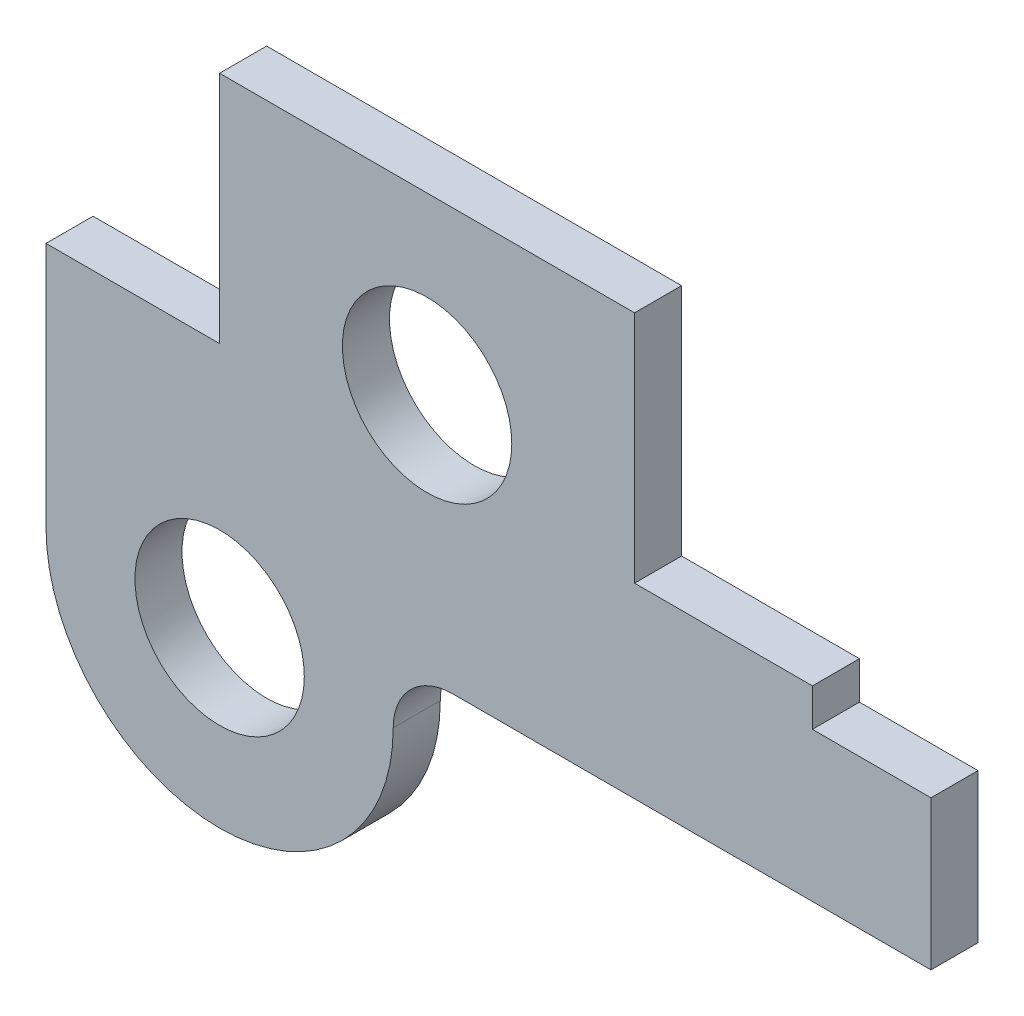
SolidWorks part; units mm, degrees
ref_plane "Front Plane" through (0, 0, 0) normal (0, 0, 1) x (1, 0, 0)
ref_plane "Top Plane" through (0, 0, 0) normal (0, 1, 0) x (1, 0, 0)
ref_plane "Right Plane" through (0, 0, 0) normal (1, 0, 0) x (0, 0, -1)
sketch "Sketch1" plane through (0, 0, 0) normal (0, 0, 1) x (1, 0, 0)
  line L4 (149.2875, 39.2875) -> (149.2875, 64.4375)
  line L9 (29.2875, 29.2875) -> (99.2875, 29.2875) construction
  line L10 (0, 70.7875) -> (29.2875, 70.7875)
  line L11 (15, 15) -> (43.575, 15) construction
  line L12 (29.2875, 70.7875) -> (29.2875, 110.2875)
  line L13 (64.2875, 29.2875) -> (64.2875, 80.7875) construction
  line L14 (15, 15) -> (15, 43.575) construction
  line L15 (15, 43.575) -> (43.575, 43.575) construction
  line L16 (43.575, 15) -> (43.575, 43.575) construction
  line L17 (15, 15) -> (43.575, 43.575) construction
  line L18 (15, 43.575) -> (43.575, 15) construction
  line L19 (68.575, 39.2875) -> (149.2875, 39.2875)
  line L20 (0, 29.2875) -> (0, 0) construction
  line L21 (0, 0) -> (29.2875, 0) construction
  line L22 (29.2875, 29.2875) -> (29.2875, 80.7875) construction
  line L26 (99.2875, 110.2875) -> (29.2875, 110.2875)
  line L29 (129.2875, 70.7875) -> (99.2875, 70.7875)
  line L30 (99.2875, 70.7875) -> (99.2875, 110.2875)
  line L31 (149.2875, 64.4375) -> (129.2875, 64.4375)
  line L32 (129.2875, 64.4375) -> (129.2875, 70.7875)
  line L33 (58.575, 29.2875) -> (68.575, 29.2875) construction
  line L34 (68.575, 29.2875) -> (68.575, 39.2875) construction
  line L36 (0, 29.2875) -> (0, 70.7875)
  line L37 (29.2875, 80.7875) -> (64.2875, 80.7875) construction
  circle A1 centre (64.2875, 80.7875) radius 14.2875
  circle A2 centre (29.2875, 29.2875) radius 6.35 construction
  circle A3 centre (29.2875, 29.2875) radius 14.2875
  circle A4 centre (64.2875, 80.7875) radius 19.05 construction
  arc A5 (0, 29.2875) -> (58.575, 29.2875) centre (29.2875, 29.2875) ccw
  arc A6 (68.575, 39.2875) -> (58.575, 29.2875) centre (68.575, 29.2875) ccw
  circle A10 centre (64.2875, 80.7875) radius 29.5 construction
  circle A11 centre (99.2875, 29.2875) radius 14.2875 construction
  circle A12 centre (64.2875, 80.7875) radius 30.1625 construction
  point P0 (58.575, 29.9604)
  dimension "D1" = 12.7
  dimension "D4" = 28.575
  dimension "D5" = 28.575
  dimension "D7" = 38.1
  dimension "D12" = 20
  dimension "D3" = 50
  dimension "D11" = 59
  dimension "D8" = 60.325
  dimension "D6" = 70
  dimension "D9" = 35
  dimension "D10" = 29.2875
  dimension "D13" = 51.5
  dimension "D17" = 35
  dimension "D18" = 10
  dimension "D19" = 20
  dimension "D20" = 6.35
extrude "Boss-Extrude1" add sketch "Sketch1" along normal blind 7.9375
